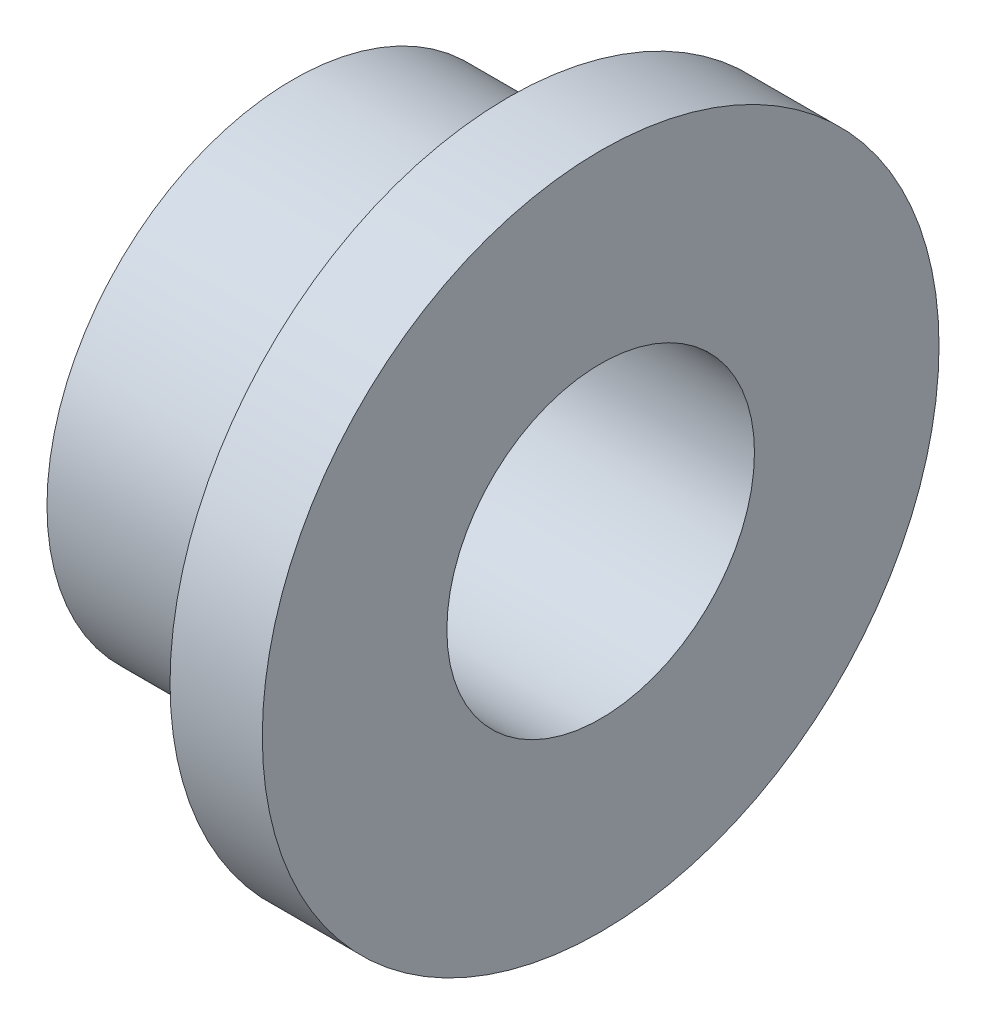
SolidWorks part; units mm, degrees
material "PA Type 6"
ref_plane "Front Plane" through (0, 0, 0) normal (0, 0, 1) x (1, 0, 0)
ref_plane "Top Plane" through (0, 0, 0) normal (0, 1, 0) x (1, 0, 0)
ref_plane "Right Plane" through (0, 0, 0) normal (1, 0, 0) x (0, 0, -1)
sketch "Sketch1" plane through (0, 0, 0) normal (0, 0, 1) x (1, 0, 0)
  line L0 (0, 8) -> (7, 8)
  line L1 (7, 8) -> (7, 11)
  line L2 (7, 11) -> (10, 11)
  line L3 (10, 11) -> (10, 5)
  line L4 (10, 5) -> (0, 5)
  line L5 (0, 5) -> (0, 8)
  line L6 (0, 0) -> (8.7927, 0) construction
  dimension "D1" = 10
  dimension "D2" = 5
  dimension "D3" = 8
  dimension "D4" = 11
  dimension "D5" = 3
revolve "Revolve1" add sketch "Sketch1" angle 360 about L6
